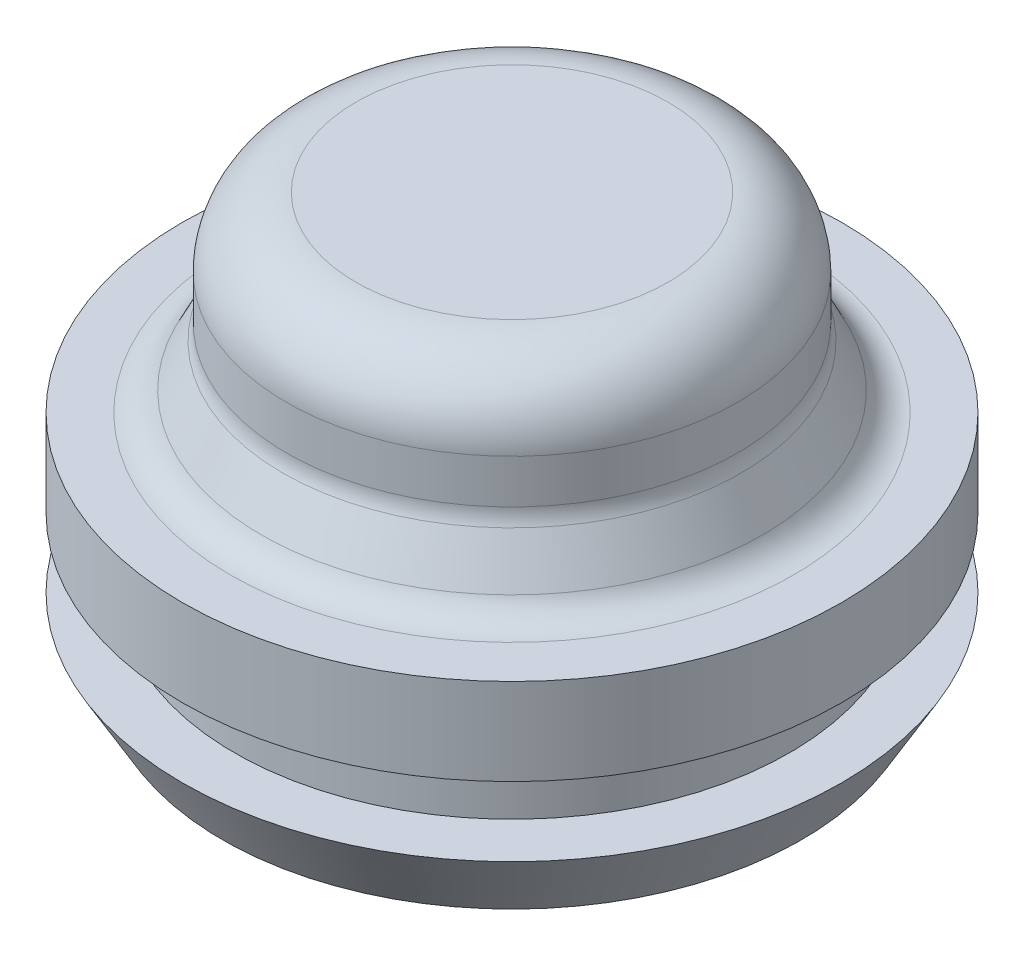
SolidWorks part; units mm, degrees
material "PA Type 6"
ref_plane "Plan de face" through (0, 0, 0) normal (0, 0, 1) x (1, 0, 0)
ref_plane "Plan de dessus" through (0, 0, 0) normal (0, 1, 0) x (1, 0, 0)
ref_plane "Plan de droite" through (0, 0, 0) normal (1, 0, 0) x (0, 0, -1)
sketch "Esquisse1" plane through (0, 0, 0) normal (0, 0, 1) x (1, 0, 0)
  line L0 (0, 0) -> (0, 54.1323) construction
  line L1 (8.3453, 0) -> (6.3, 0)
  line L2 (8.3453, 0) -> (9.5, 2)
  line L3 (9.5, 2) -> (8, 2)
  line L4 (8, 2) -> (8, 4)
  line L5 (8, 4) -> (9.5, 4)
  line L6 (9.5, 4) -> (9.5, 6.5)
  line L7 (9.5, 6.5) -> (8.118, 6.5)
  line L8 (6.5, 8.7361) -> (6.5, 10)
  line L9 (4.5, 12) -> (0, 12)
  line L10 (9.5, 2) -> (9.5, -5.2874) construction
  line L11 (6.3, 0) -> (5.405, 0.895)
  line L12 (5.3, 1.8983) -> (5.3, -3.2272) construction
  line L14 (4.3, 11) -> (0, 11)
  line L15 (0, 11) -> (0, 12)
  line L16 (7.2236, 7.0528) -> (6.6056, 8.2889)
  line L17 (5.3, 6.3125) -> (5.3, 10)
  arc A0 (6.5, 10) -> (4.5, 12) centre (4.5, 10) ccw
  arc A1 (4.3, 11) -> (5.3, 10) centre (4.3, 10) cw
  arc A2 (6.6056, 8.2889) -> (6.5, 8.7361) centre (7.5, 8.7361) cw
  arc A3 (8.118, 6.5) -> (7.2236, 7.0528) centre (8.118, 7.5) cw
  arc A4 (5.405, 0.895) -> (5.3, 6.3125) centre (0, 3.5) ccw
  point P21 (6.5, 12)
  point P27 (6.5, 8.5)
  point P30 (7.5, 6.5)
  dimension "D1" = 2
  dimension "D13" = 2
  dimension "D16" = 1
  dimension "D18" = 1
  dimension "D19" = 12
  dimension "D2" = 2
  dimension "D3" = 2.5
  dimension "D4" = 2
  dimension "D5" = 45
  dimension "D6" = 8
  dimension "D7" = 30
  dimension "D8" = 9.5
  dimension "D11" = 1
  dimension "D12" = 12
  dimension "D14" = 6.5
  dimension "D15" = 9.5
  dimension "D17" = 7.5
  dimension "D20" = 3.5
revolve "Révolution1" add sketch "Esquisse1" angle 360 about L0
